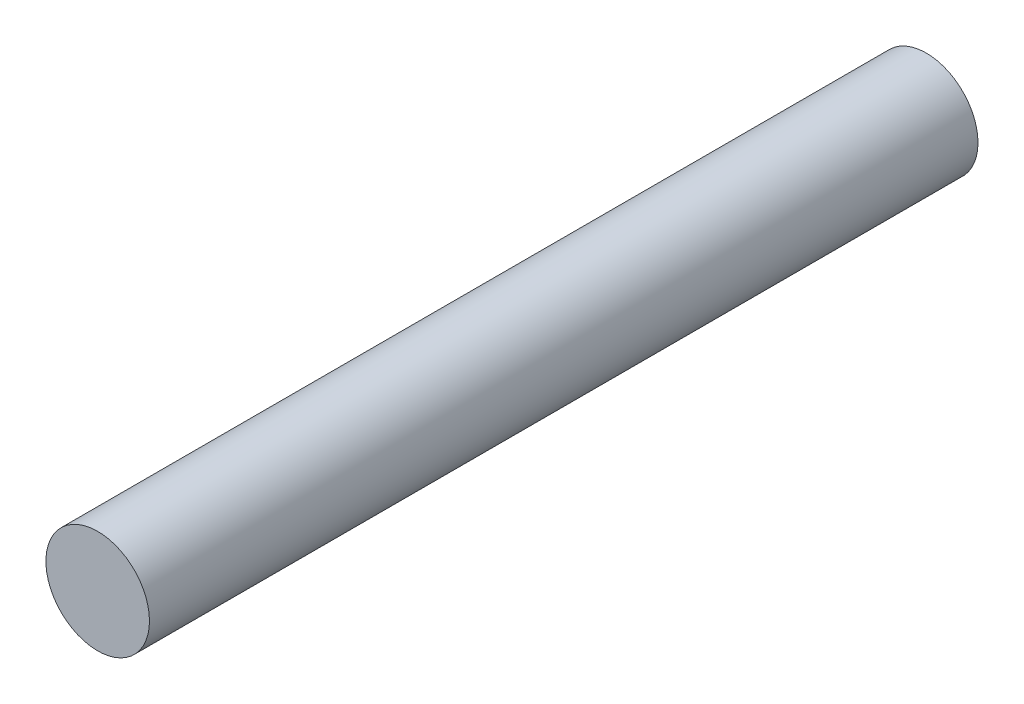
SolidWorks part; units mm, degrees
ref_plane "Plan de face" through (0, 0, 0) normal (0, 0, 1) x (1, 0, 0)
ref_plane "Plan de dessus" through (0, 0, 0) normal (0, 1, 0) x (1, 0, 0)
ref_plane "Plan de droite" through (0, 0, 0) normal (1, 0, 0) x (0, 0, -1)
sketch "Esquisse1" plane through (0, 0, 0) normal (0, 0, 1) x (1, 0, 0)
  circle A0 centre (0, 0) radius 2.5
  dimension "D1" = 5
extrude "Boss.-Extru.1" add sketch "Esquisse1" along normal blind 40
